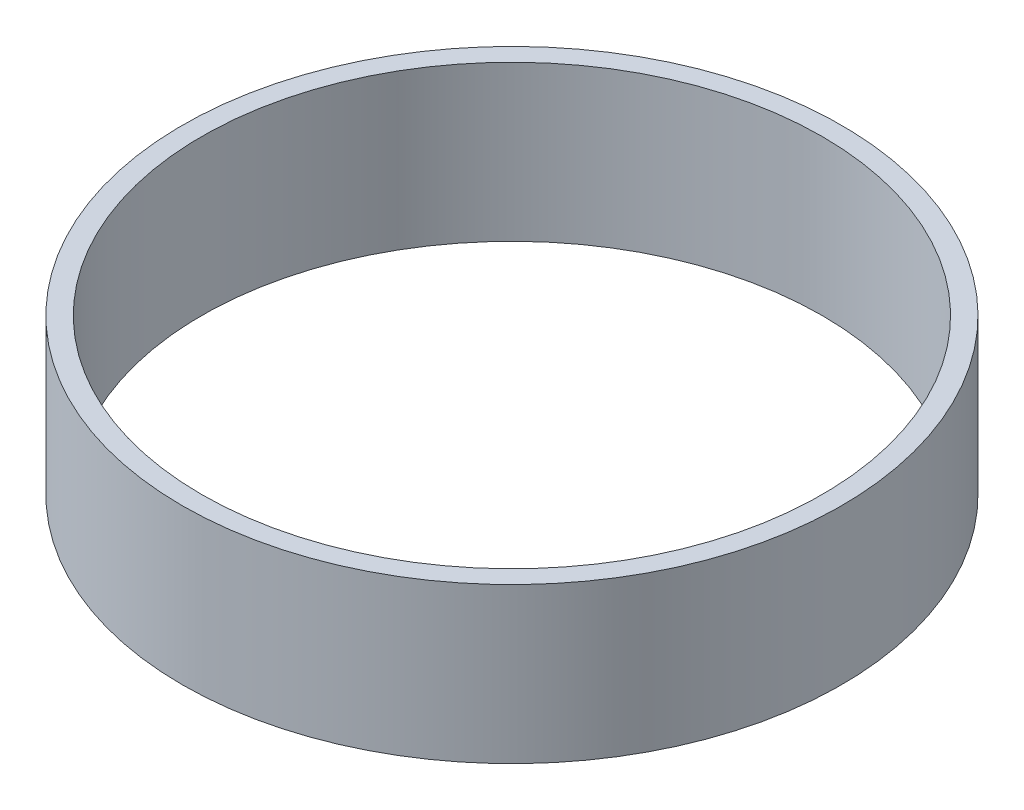
SolidWorks part; units mm, degrees
ref_plane "Plan de face" through (0, 0, 0) normal (0, 0, 1) x (1, 0, 0)
ref_plane "Plan de dessus" through (0, 0, 0) normal (0, 1, 0) x (1, 0, 0)
ref_plane "Plan de droite" through (0, 0, 0) normal (1, 0, 0) x (0, 0, -1)
sketch "Esquisse1" plane through (0, 0, 0) normal (0, 1, 0) x (1, 0, 0)
  circle A0 centre (0, 0) radius 85
  circle A1 centre (0, 0) radius 80
  dimension "D1" = 170
  dimension "D2" = 160
extrude "Boss.-Extru.1" add sketch "Esquisse1" along normal blind 40
